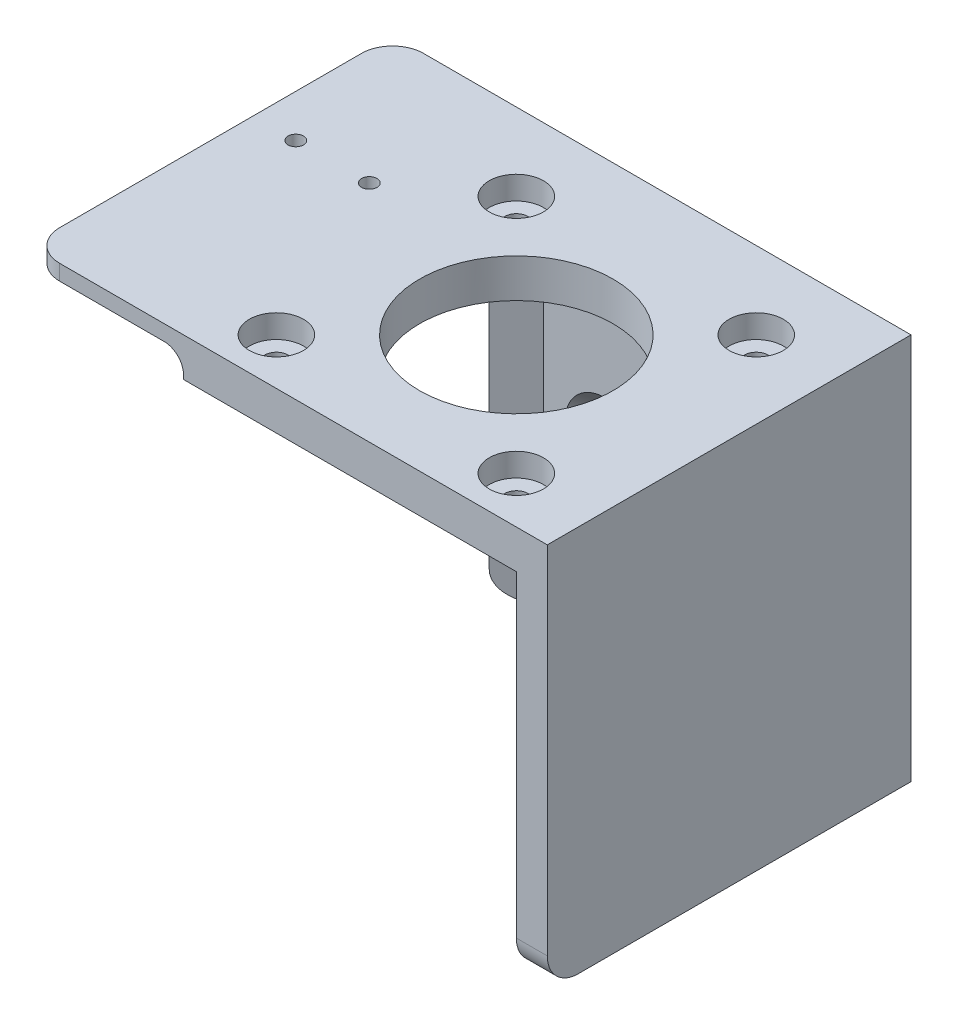
SolidWorks part; units mm, degrees
ref_plane "正面" through (0, 0, 0) normal (0, 0, 1) x (1, 0, 0)
ref_plane "平面" through (0, 0, 0) normal (0, 1, 0) x (1, 0, 0)
ref_plane "右側面" through (0, 0, 0) normal (1, 0, 0) x (0, 0, -1)
sketch "ｽｹｯﾁ2" plane through (0, 0, 0) normal (0, 0, 1) x (1, 0, 0)
  line L1 (0, 0) -> (47, 0)
  line L2 (0, 0) -> (0, 47)
  line L3 (0, 47) -> (47, 47)
  line L4 (47, 0) -> (47, 47)
  dimension "D1" = 47
  dimension "D2" = 47
extrude "ﾎﾞｽ - 押し出し1" add sketch "ｽｹｯﾁ2" along normal blind 4
sketch "ｽｹｯﾁ3" plane through (0, 0, 4) normal (0, 0, 1) x (1, 0, 0)
  line L0 (47, 0) -> (47, 47) construction
  line L1 (0, 47) -> (47, 47)
  line L2 (0, 47) -> (0, 45)
  line L3 (0, 45) -> (47, 45)
  line L4 (47, 47) -> (47, 45)
  dimension "D1" = 2
extrude "ﾎﾞｽ - 押し出し2" add sketch "ｽｹｯﾁ3" along normal blind 43
sketch "ｽｹｯﾁ4" plane through (0, 0, 4) normal (0, 0, 1) x (1, 0, 0)
  line L0 (0, 0) -> (47, 0) construction
  line L1 (47, 45) -> (43, 45)
  line L2 (47, 45) -> (47, 0)
  line L3 (47, 0) -> (43, 0)
  line L4 (43, 45) -> (43, 0)
  dimension "D1" = 4
extrude "ﾎﾞｽ - 押し出し3" add sketch "ｽｹｯﾁ4" along normal blind 43
sketch "ｽｹｯﾁ5" plane through (0, 45, 0) normal (0, -1, 0) x (1, 0, 0)
  line L0 (0, 47) -> (0, 4) construction
  line L1 (43, 47) -> (43, 4) construction
  line L2 (0, 47) -> (43, 47) construction
  line L3 (0, 4) -> (43, 4) construction
  circle A0 centre (21.5, 25.5) radius 12.5
  point P4 (0, 25.5)
  dimension "D1" = 21.5
  dimension "D2" = 21.5
  dimension "D3" = 21.5
  dimension "D4" = 21.5
extrude "ｶｯﾄ - 押し出し1" cut sketch "ｽｹｯﾁ5" against normal through all
sketch "ｽｹｯﾁ7" plane through (0, 47, 0) normal (0, 1, 0) x (1, 0, 0)
  line L0 (21.0324, 0) -> (21.5, 0) construction
  line L1 (47, 0) -> (0, 0) construction
  line L2 (21.5, 0) -> (21.5, -45.6025) construction
  line L3 (0, -47) -> (0, 0) construction
  line L4 (0, -25.5) -> (47, -25.5) construction
  line L5 (47, -47) -> (47, 0) construction
  line L6 (47, -47) -> (0, -47) construction
  point P0 (6, -10)
  point P14 (6, -41)
  point P15 (37, -41)
  point P17 (37, -10)
  dimension "D1" = 21.5
  dimension "D2" = 15.5
  dimension "D3" = 21.5
  dimension "D4" = 15.5
  dimension "D5" = 15.5
  dimension "D6" = 15.5
  dimension "D7" = 15.5
  dimension "D8" = 15.5
  dimension "D9" = 15.5
  dimension "D10" = 15.5
hole_wizard "M3x0.5 ねじ穴2" positions "ｽｹｯﾁ8" profile "ｽｹｯﾁ9" tap size "M3x0.5" standard "JIS" end condition up to next
sketch "ｽｹｯﾁ8" plane through (0, 47, 0) normal (0, 1, 0) x (1, 0, 0)
  point P0 (6, -10)
  point P3 (37, -10)
  point P6 (37, -41)
  point P9 (6, -41)
sketch "ｽｹｯﾁ9" plane through (6, 47, 10) normal (1, 0, 0) x (0, 0, 1)
  line L0 (0, 0) -> (0, 2)
  line L1 (0, 2) -> (1.5, 2)
  line L2 (1.5, 2) -> (1.5, 0)
  line L5 (1.5, 0) -> (0, 0)
  line L11 (0, -6.35) -> (0, 107.95) construction
  dimension "ねじ山の主要直径" = 3
  dimension "次ｻｰﾌｪｽまでのねじ下穴ﾄﾞﾘﾙの深さ" = 2
sketch "ｽｹｯﾁ10" plane through (0, 0, 4) normal (0, 0, 1) x (1, 0, 0)
  line L0 (0, 22) -> (43, 22) construction
  line L1 (0, 45) -> (0, 0) construction
  line L2 (43, 45) -> (43, 0) construction
  line L3 (0, 0) -> (43, 0) construction
  line L5 (21.5, 45) -> (21.5, 0) construction
  line L6 (0, 45) -> (43, 45) construction
  line L7 (0, 47) -> (47, 47) construction
  point P12 (21.5, 32)
  point P13 (31.5, 22)
  point P14 (21.5, 12)
  point P15 (11.5, 22)
  point P16 (21.5, 22)
  dimension "D1" = 25
  dimension "D2" = 21.5
  dimension "D3" = 10
  dimension "D4" = 10
  dimension "D5" = 10
  dimension "D6" = 10
hole_wizard "M5 平皿頭ねじ用皿穴1" positions "ｽｹｯﾁ13" profile "ｽｹｯﾁ14" countersink size "M5" standard "JIS" end condition up to next
sketch "ｽｹｯﾁ13" plane through (0, 0, 4) normal (0, 0, 1) x (1, 0, 0)
  point P0 (11.5, 22)
  point P3 (21.5, 32)
  point P9 (31.5, 22)
  point P12 (21.5, 12)
sketch "ｽｹｯﾁ14" plane through (11.5, 22, 4) normal (1, 0, 0) x (0, -1, 0)
  line L0 (0, 0) -> (0, 4)
  line L1 (0, 4) -> (2.75, 4)
  line L2 (2.75, 4) -> (2.75, 2.45)
  line L3 (2.75, 2.45) -> (5.2, 0)
  line L5 (5.2, 0) -> (0, 0)
  line L6 (-2.75, 2.45) -> (-5.2, 0) construction
  line L11 (0, -6.35) -> (0, 107.95) construction
  dimension "通し穴の直径" = 5.5
  dimension "通し穴の深さ" = 4
  dimension "表面の皿穴の直径" = 10.4
  dimension "表面の皿穴の角度" = 90
sketch "ｽｹｯﾁ17" plane through (0, 45, 0) normal (0, -1, 0) x (1, 0, 0)
  line L0 (43, 4) -> (39.5, 4)
  line L1 (0, 4) -> (43, 4) construction
  line L2 (39.5, 4) -> (43, 7.5)
  line L3 (43, 47) -> (43, 4) construction
  line L4 (43, 7.5) -> (43, 4)
  dimension "D1" = 3.5
  dimension "D2" = 3.5
extrude "ﾎﾞｽ - 押し出し6" add sketch "ｽｹｯﾁ17" along normal blind 45
sketch "ｽｹｯﾁ19" plane through (0, 45, 0) normal (0, -1, 0) x (1, 0, 0)
  line L0 (0, 4) -> (3.5, 4)
  line L1 (0, 4) -> (39.5, 4) construction
  line L2 (3.5, 4) -> (0, 7.5)
  line L3 (0, 47) -> (0, 4) construction
  line L4 (0, 7.5) -> (0, 4)
  dimension "D1" = 3.5
  dimension "D2" = 3.5
extrude "ﾎﾞｽ - 押し出し7" add sketch "ｽｹｯﾁ19" along normal blind 45
sketch "ｽｹｯﾁ23" plane through (0, 47, 0) normal (0, 1, 0) x (1, 0, 0)
  line L0 (0, -47) -> (0, 0) construction
  line L1 (47, 0) -> (-20, 0)
  line L2 (47, 0) -> (47, -47)
  line L3 (47, -47) -> (-20, -47)
  line L4 (-20, 0) -> (-20, -47)
  circle A0 centre (6, -10) radius 3.5
  circle A1 centre (6, -41) radius 3.5
  circle A2 centre (37, -10) radius 3.5
  circle A3 centre (37, -41) radius 3.5
  circle A4 centre (21.5, -25.5) radius 12.5
  dimension "D1" = 20
  dimension "D2" = 47
extrude "ﾎﾞｽ - 押し出し10" add sketch "ｽｹｯﾁ23" along normal blind 3
sketch "ｽｹｯﾁ24" plane through (0, 50, 0) normal (0, 1, 0) x (1, 0, 0)
  point P0 (-5, -18)
  point P1 (-14.5, -18)
  dimension "D1" = 7.5
  dimension "D2" = 7.5
  dimension "D3" = 9.5
  dimension "D4" = 5
hole_wizard "M2x0.4 ねじ穴1" positions "ｽｹｯﾁ25" profile "ｽｹｯﾁ26" tap size "M2x0.4" standard "JIS" end condition up to next
sketch "ｽｹｯﾁ25" plane through (0, 50, 0) normal (0, 1, 0) x (1, 0, 0)
  point P0 (-5, -18)
  point P3 (-14.5, -18)
sketch "ｽｹｯﾁ26" plane through (-5, 50, 18) normal (1, 0, 0) x (0, 0, 1)
  line L0 (0, 0) -> (0, 3)
  line L1 (0, 3) -> (1, 3)
  line L2 (1, 3) -> (1, 0)
  line L5 (1, 0) -> (0, 0)
  line L11 (0, -6.35) -> (0, 107.95) construction
  dimension "ねじ山の主要直径" = 2
  dimension "次ｻｰﾌｪｽまでのねじ下穴ﾄﾞﾘﾙの深さ" = 3
sketch "ｽｹｯﾁ27" plane through (-20, 0, 0) normal (-1, 0, 0) x (0, 0, 1)
  line L1 (0, 47) -> (47, 47)
  line L2 (0, 47) -> (0, 48)
  line L3 (0, 48) -> (47, 48)
  line L4 (47, 47) -> (47, 48)
  dimension "D1" = 47
  dimension "D2" = 1
extrude "ｶｯﾄ - 押し出し2" cut sketch "ｽｹｯﾁ27" against normal blind 20
fillet "ﾌｨﾚｯﾄ1" radius 2.5 1 edges at (0, 48, 23.5)
fillet "ﾌｨﾚｯﾄ2" radius 4 4 edges at (-20, 49, 47) (-20, 49, 0) (0, 0, 3.75) (45, 0, 47)
